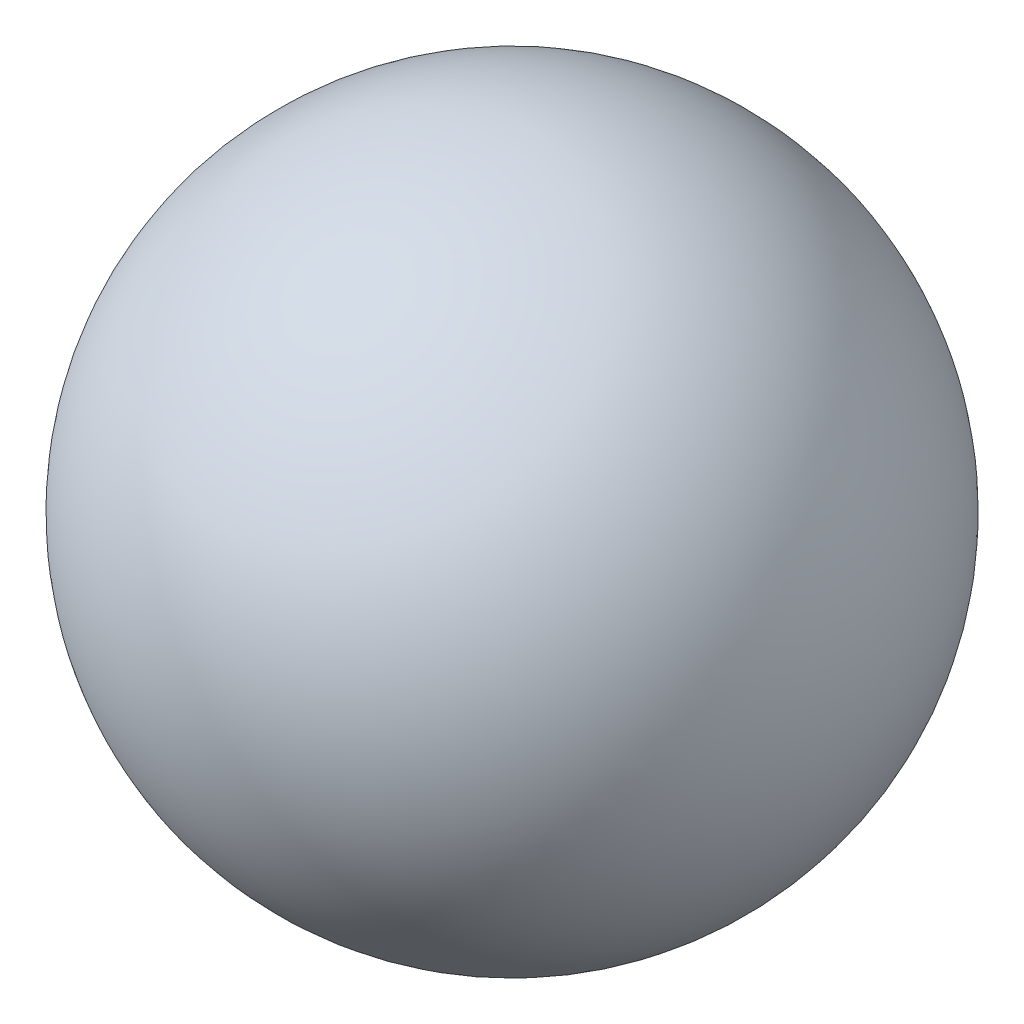
SolidWorks part; units mm, degrees
ref_plane "Plano frontal" through (0, 0, 0) normal (0, 0, 1) x (1, 0, 0)
ref_plane "Plano superior" through (0, 0, 0) normal (0, 1, 0) x (1, 0, 0)
ref_plane "Plano direito" through (0, 0, 0) normal (1, 0, 0) x (0, 0, -1)
sketch "Esboço1" plane through (0, 0, 0) normal (0, 1, 0) x (1, 0, 0)
  line L0 (0, -0.7375) -> (0, -10.2625)
  line L1 (0, -0.7375) -> (0, -10.2625) construction
  arc A0 (0, -10.2625) -> (0, -0.7375) centre (0, -5.5) ccw
revolve "Revolução1" add sketch "Esboço1" angle 360 about L1
